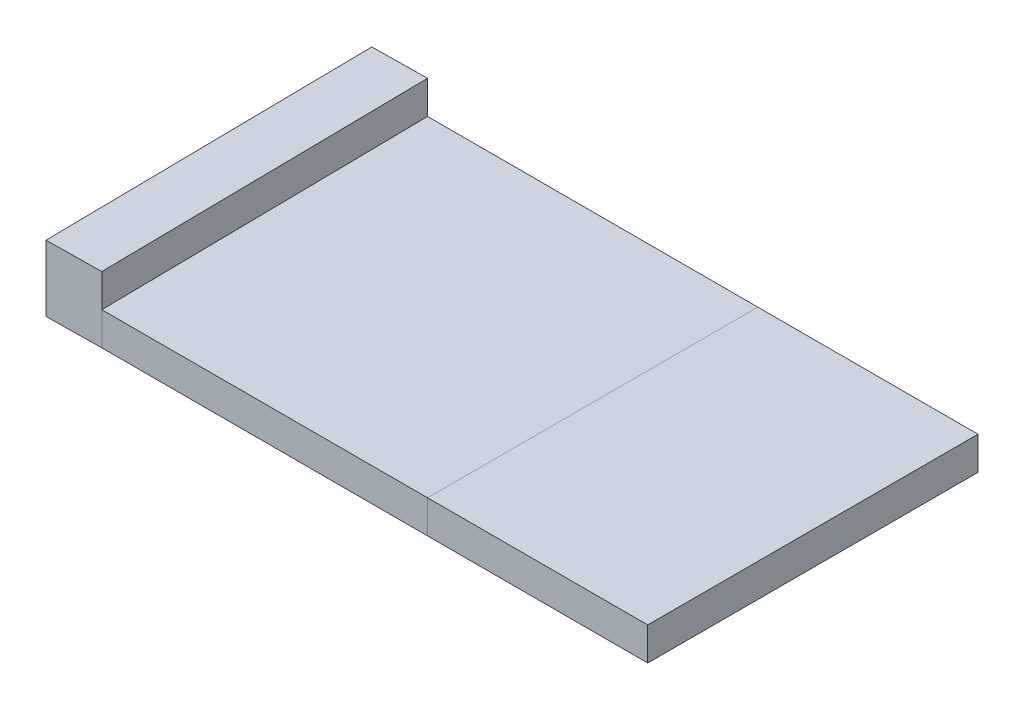
SolidWorks part; units mm, degrees
ref_plane "前视基准面" through (0, 0, 0) normal (0, 0, 1) x (1, 0, 0)
ref_plane "上视基准面" through (0, 0, 0) normal (0, 1, 0) x (1, 0, 0)
ref_plane "右视基准面" through (0, 0, 0) normal (1, 0, 0) x (0, 0, -1)
sketch "草图1" plane through (0, 0, 0) normal (0, 1, 0) x (1, 0, 0)
  line L0 (0, 0) -> (295.9532, 0)
  line L1 (295.9532, 0) -> (295.9532, 300)
  line L2 (295.9532, 300) -> (-4.0468, 300)
  line L3 (-4.0468, 300) -> (0, 0)
  dimension "D1" = 300
  dimension "D2" = 300
extrude "凸台-拉伸1" add sketch "草图1" along normal blind 30
sketch "草图2" plane through (295.9532, 0, 0) normal (1, 0, 0) x (0, 0, -1)
  line L4 (0, 0) -> (300, 0)
  line L5 (300, 0) -> (300, 30)
  line L6 (300, 30) -> (0, 30)
  line L7 (0, 30) -> (0, 0)
  line L8 (0, 0) -> (300, 0)
  line L9 (300, 0) -> (300, 30)
  line L10 (300, 30) -> (0, 30)
  line L11 (0, 30) -> (0, 0)
  dimension "D1" = 0
extrude "凸台-拉伸2" add sketch "草图2" along normal blind 200 separate body
sketch "草图3" plane through (0, 0, 0) normal (-0.9999, 0, 0.0135) x (0.0135, 0, 0.9999)
  line L0 (0, 0) -> (0, 60)
  line L1 (0, 60) -> (-300.0273, 60)
  line L2 (-300.0273, 60) -> (-300.0273, 0)
  line L3 (-300.0273, 0) -> (0, 0)
  dimension "D1" = 60
extrude "凸台-拉伸3" add sketch "草图3" along normal blind 50
